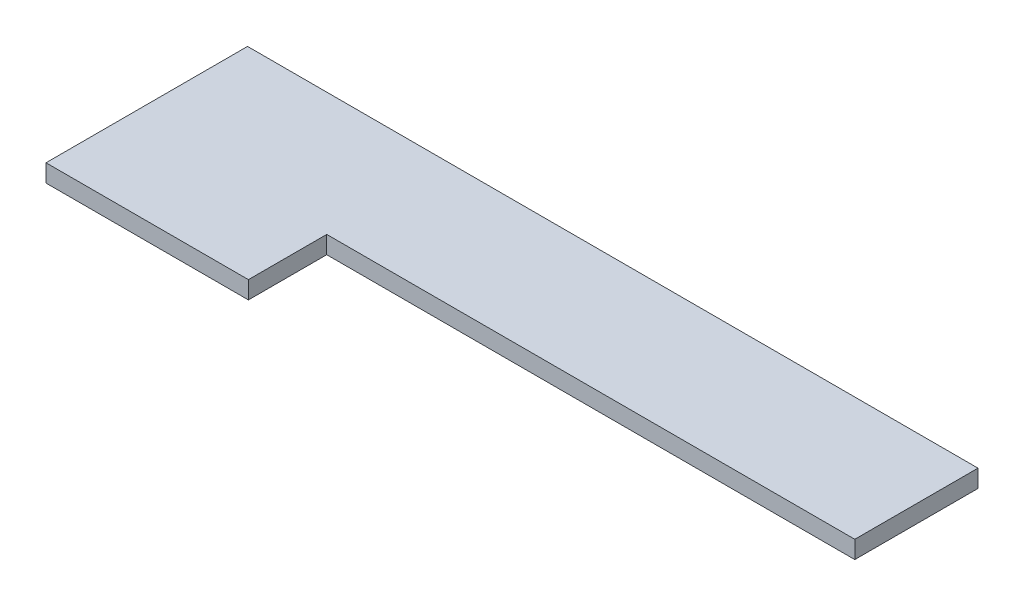
SolidWorks part; units mm, degrees
ref_plane "Спереди" through (0, 0, 0) normal (0, 0, 1) x (1, 0, 0)
ref_plane "Сверху" through (0, 0, 0) normal (0, 1, 0) x (1, 0, 0)
ref_plane "Справа" through (0, 0, 0) normal (1, 0, 0) x (0, 0, -1)
sketch "Эскиз1" plane through (0, 0, 0) normal (0, 1, 0) x (1, 0, 0)
  line L0 (6.5, 7.73) -> (36.5, 7.73)
  line L1 (-5, 7.73) -> (6.5, 7.73)
  line L2 (-5, 7.73) -> (-5, -3.72)
  line L3 (-5, -3.72) -> (6.5, -3.72)
  line L4 (6.5, 0.73) -> (6.5, -3.72)
  line L5 (36.5, 7.73) -> (36.5, 0.73)
  line L6 (36.5, 0.73) -> (6.5, 0.73)
  point P0 (0, 0)
extrude "Бобышка-Вытянуть1" add sketch "Эскиз1" along normal blind 1
